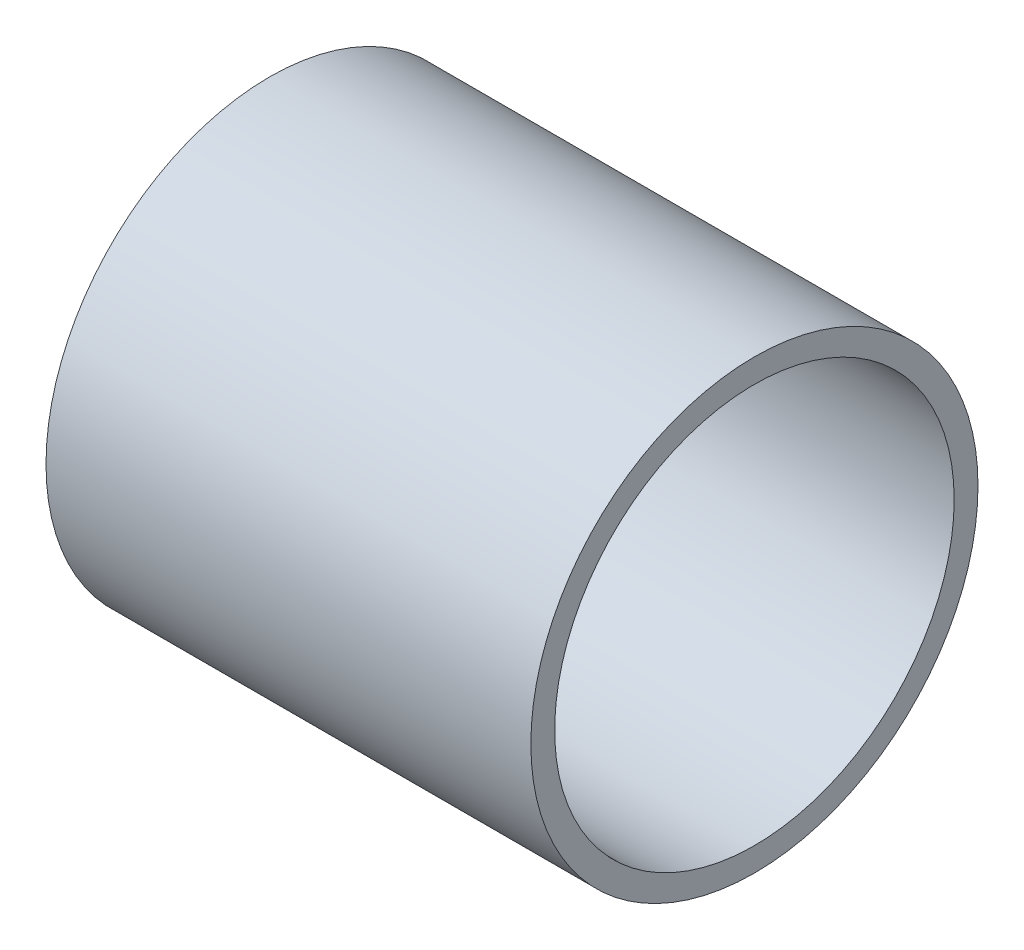
SolidWorks part; units mm, degrees
material "Galvanized Steel"
ref_plane "Front Plane" through (0, 0, 0) normal (0, 0, 1) x (1, 0, 0)
ref_plane "Top Plane" through (0, 0, 0) normal (0, 1, 0) x (1, 0, 0)
ref_plane "Right Plane" through (0, 0, 0) normal (1, 0, 0) x (0, 0, -1)
sketch "Sketch3" plane through (0, 0, 0) normal (1, 0, 0) x (0, 0, -1)
  circle A0 centre (0, 0) radius 10.4648
  circle A1 centre (0, 0) radius 11.7126
  dimension "D1" = 20.9296
  dimension "D2" = 23.4251
extrude "Boss-Extrude1" add sketch "Sketch3" along normal blind 25.4
